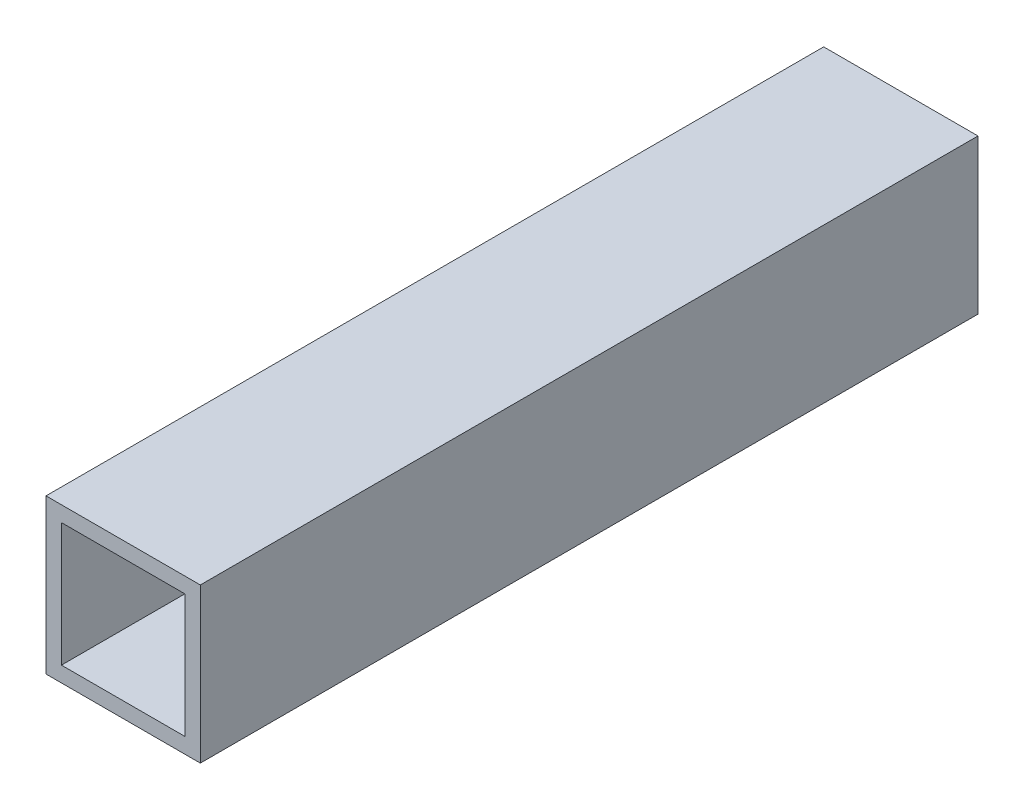
SolidWorks part; units mm, degrees
material "Brass"
ref_plane "Front Plane" through (0, 0, 0) normal (0, 0, 1) x (1, 0, 0)
ref_plane "Top Plane" through (0, 0, 0) normal (0, 1, 0) x (1, 0, 0)
ref_plane "Right Plane" through (0, 0, 0) normal (1, 0, 0) x (0, 0, -1)
sketch "Sketch1" plane through (0, 0, 0) normal (0, 0, 1) x (1, 0, 0)
  line L1 (-1.9844, 1.9844) -> (1.9844, 1.9844)
  line L2 (-1.9844, 1.9844) -> (-1.9844, -1.9844)
  line L3 (-1.9844, -1.9844) -> (1.9844, -1.9844)
  line L4 (1.9844, 1.9844) -> (1.9844, -1.9844)
  line L5 (-1.9844, 1.9844) -> (1.9844, -1.9844) construction
  line L6 (-1.9844, -1.9844) -> (1.9844, 1.9844) construction
  point P0 (0, 0)
  dimension "D1" = 3.9688
extrude "Boss-Extrude1" add sketch "Sketch1" along normal mid plane 20
sketch "Sketch2" plane through (0, 0, 10) normal (0, 0, 1) x (1, 0, 0)
  line L1 (-1.5875, 1.5875) -> (1.5875, 1.5875)
  line L2 (-1.5875, 1.5875) -> (-1.5875, -1.5875)
  line L3 (-1.5875, -1.5875) -> (1.5875, -1.5875)
  line L4 (1.5875, 1.5875) -> (1.5875, -1.5875)
  line L5 (-1.5875, 1.5875) -> (1.5875, -1.5875) construction
  line L6 (-1.5875, -1.5875) -> (1.5875, 1.5875) construction
  point P0 (0, 0)
  dimension "D1" = 3.175
extrude "Cut-Extrude1" cut sketch "Sketch2" against normal through all
